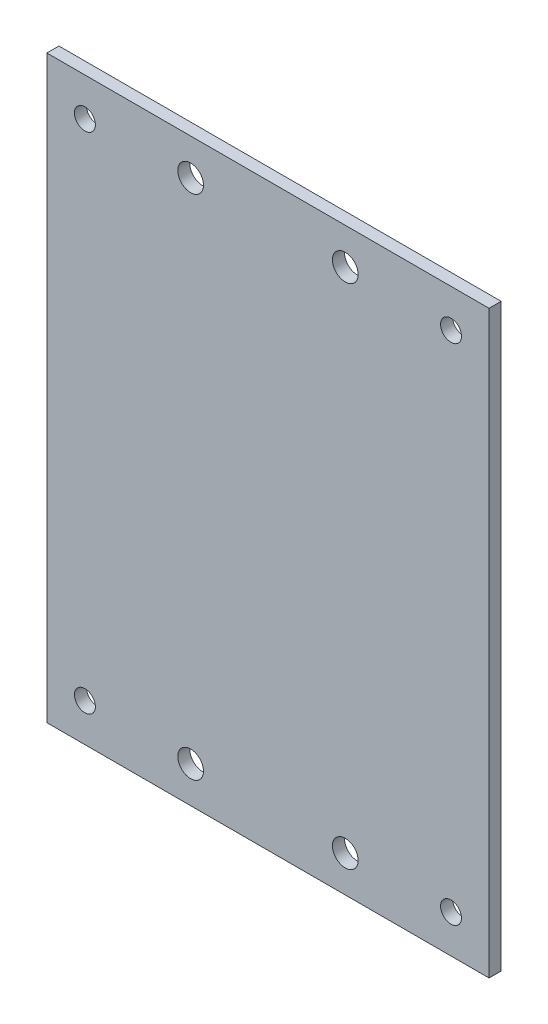
SolidWorks part; units mm, degrees
material "Acrylic (Medium-high impact)"
ref_plane "Front" through (0, 0, 0) normal (0, 0, 1) x (1, 0, 0)
ref_plane "Top" through (0, 0, 0) normal (0, 1, 0) x (1, 0, 0)
ref_plane "Right" through (0, 0, 0) normal (1, 0, 0) x (0, 0, -1)
sketch "Sketch1" plane through (0, 0, 0) normal (0, 0, 1) x (1, 0, 0)
  line L1 (0, 0) -> (116.2, 0)
  line L2 (0, 0) -> (0, 152.4)
  line L3 (0, 152.4) -> (116.2, 152.4)
  line L4 (116.2, 0) -> (116.2, 152.4)
  dimension "D1" = 152.4
  dimension "D2" = 116.2
extrude "Boss-Extrude1" add sketch "Sketch1" along normal blind 3.175
hole_wizard "M5 Clearance Hole1" positions "Sketch2" profile "Sketch3" hole size "M5" standard "ANSI Metric" end condition up to next
sketch "Sketch2" plane through (0, 0, 3.175) normal (0, 0, 1) x (1, 0, 0)
  line L0 (10, 142.4) -> (0, 142.4) construction
  line L1 (0, 152.4) -> (0, 0) construction
  line L3 (10, 152.4) -> (10, 142.4) construction
  line L4 (116.2, 152.4) -> (0, 152.4) construction
  line L6 (106.2, 152.4) -> (106.2, 142.4) construction
  line L7 (106.2, 142.4) -> (116.2, 142.4) construction
  line L8 (116.2, 0) -> (116.2, 152.4) construction
  line L10 (10, 0) -> (10, 10) construction
  line L11 (50, 0) -> (-50, 0) construction
  line L12 (10, 10) -> (0, 10) construction
  line L13 (0, -50) -> (0, 50) construction
  line L15 (116.2, 10) -> (106.2, 10) construction
  line L16 (106.2, 10) -> (106.2, 0) construction
  line L17 (0, 0) -> (116.2, 0) construction
  point P0 (10, 142.4)
  point P2 (106.2, 142.4)
  point P4 (106.2, 10)
  point P6 (10, 10)
  dimension "D1" = 10
sketch "Sketch3" plane through (10, 142.4, 3.175) normal (1, 0, 0) x (0, -1, 0)
  line L0 (0, 0) -> (0, 3.175)
  line L1 (0, 3.175) -> (2.75, 3.175)
  line L2 (2.75, 3.175) -> (2.75, 0)
  line L5 (2.75, 0) -> (0, 0)
  line L11 (0, -6.35) -> (0, 107.95) construction
  dimension "Thru Hole Dia." = 5.5
  dimension "Thru Hole Depth" = 3.175
hole_wizard "1/4 Clearance Hole1" positions "Sketch4" profile "Sketch5" hole size "1/4" standard "ANSI Inch" end condition up to next
sketch "Sketch4" plane through (0, 0, 0) normal (0, 0, -1) x (-1, 0, 0)
  line L0 (-78.42, 142.875) -> (-78.42, 152.4) construction
  line L1 (-116.2, 152.4) -> (0, 152.4) construction
  line L4 (-37.78, 142.875) -> (-37.78, 152.4) construction
  line L6 (-37.78, 9.525) -> (-37.78, 0) construction
  line L7 (0, 0) -> (-116.2, 0) construction
  line L9 (-78.42, 9.525) -> (-78.42, 0) construction
  line L11 (-78.42, 142.875) -> (-37.78, 142.875) construction
  line L13 (-78.42, 9.525) -> (-37.78, 9.525) construction
  line L15 (-78.42, 147.6375) -> (-116.2, 147.6375) construction
  line L16 (-116.2, 0) -> (-116.2, 152.4) construction
  line L18 (-37.78, 147.6375) -> (0, 147.6375) construction
  line L19 (0, 152.4) -> (0, 0) construction
  line L21 (-78.42, 4.7625) -> (-116.2, 4.7625) construction
  line L23 (-37.78, 4.7625) -> (0, 4.7625) construction
  point P0 (-78.42, 142.875)
  point P2 (-37.78, 142.875)
  point P4 (-37.78, 9.525)
  point P6 (-78.42, 9.525)
  dimension "D1" = 9.525
  dimension "D2" = 40.64
sketch "Sketch5" plane through (78.42, 142.875, 0) normal (1, 0, 0) x (0, 1, 0)
  line L0 (0, 0) -> (0, 3.175)
  line L1 (0, 3.175) -> (3.3782, 3.175)
  line L2 (3.3782, 3.175) -> (3.3782, 0)
  line L5 (3.3782, 0) -> (0, 0)
  line L11 (0, -6.35) -> (0, 107.95) construction
  dimension "Thru Hole Dia." = 6.7564
  dimension "Thru Hole Depth" = 3.175
